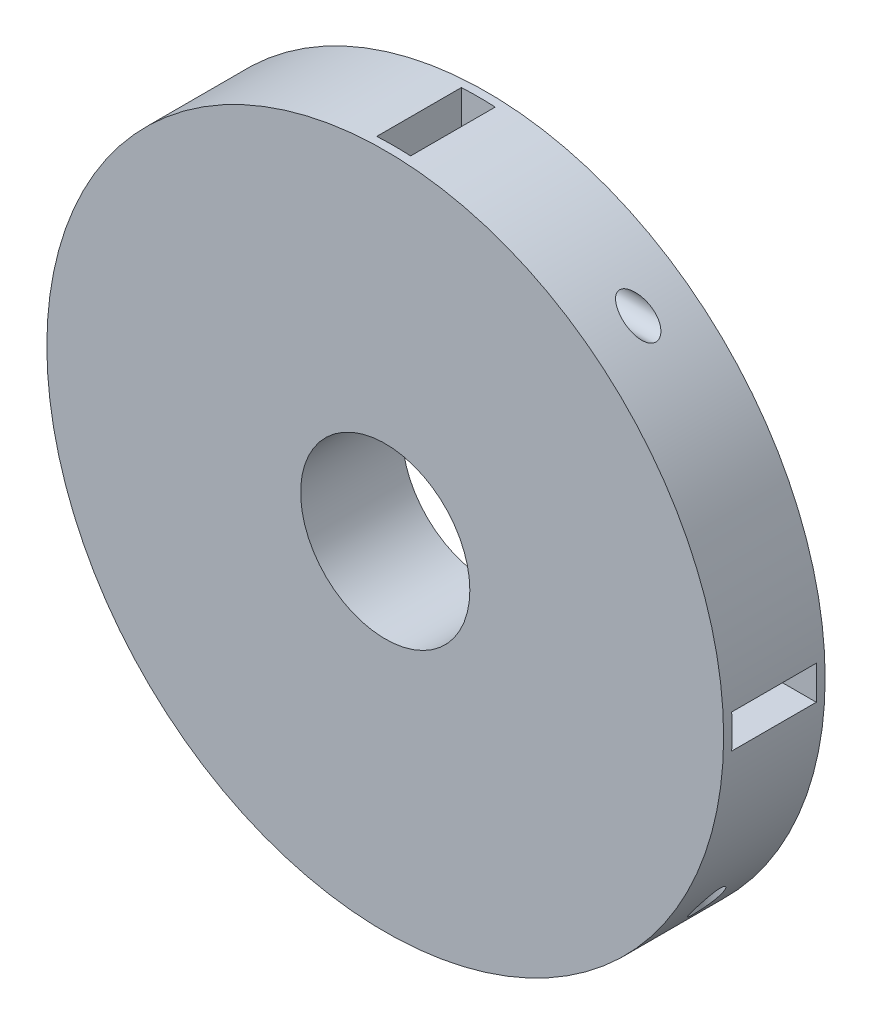
SolidWorks part; units mm, degrees
ref_plane "Front Plane" through (0, 0, 0) normal (0, 0, 1) x (1, 0, 0)
ref_plane "Top Plane" through (0, 0, 0) normal (0, 1, 0) x (1, 0, 0)
ref_plane "Right Plane" through (0, 0, 0) normal (1, 0, 0) x (0, 0, -1)
sketch "Sketch1" plane through (0, 0, 0) normal (0, 0, 1) x (1, 0, 0)
  circle A0 centre (0, 0) radius 100
  circle A1 centre (0, 0) radius 25
  dimension "D1" = 200
  dimension "D2" = 50
extrude "Boss-Extrude1" add sketch "Sketch1" along normal mid plane 30
sketch "Sketch2" plane through (0, 0, 0) normal (0, 0, 1) x (1, 0, 0)
  line L0 (0, -146.3534) -> (0, 146.3534) construction
  line L1 (187.0515, 0) -> (-187.0515, 0) construction
  line L2 (100, -29.0064) -> (100, 29.0064) construction
  line L3 (60, -5) -> (110, -5)
  line L4 (60, -5) -> (60, 5)
  line L5 (60, 5) -> (100, 5)
  line L7 (100, 5) -> (110, -5)
  line L20 (-5, -60) -> (-5, -110)
  line L21 (-5, -60) -> (5, -60)
  line L22 (5, -60) -> (5, -100)
  line L23 (5, -100) -> (-5, -110)
  line L24 (-60, 5) -> (-110, 5)
  line L25 (-60, 5) -> (-60, -5)
  line L26 (-60, -5) -> (-100, -5)
  line L27 (-100, -5) -> (-110, 5)
  line L28 (5, 60) -> (5, 110)
  line L29 (5, 60) -> (-5, 60)
  line L30 (-5, 60) -> (-5, 100)
  line L31 (-5, 100) -> (5, 110)
  circle A0 centre (0, 0) radius 100 construction
  circle A1 centre (0, 0) radius 100 construction
  point P5 (0, 0)
  point P6 (100, 0)
  point P9 (0, 0)
  point P19 (100, 0)
  point P22 (0, -100)
  point P26 (0, -100)
  point P28 (-100, 0)
  point P32 (-100, 0)
  point P34 (0, 100)
  point P38 (0, 100)
  point P40 (-5, 0.4636)
  point P41 (0, 0)
  dimension "D1" = 200
  dimension "D2" = 4
  dimension "D3" = 5
  dimension "D4" = 40
  dimension "D5" = 10
  dimension "D6" = 5
extrude "Cut-Extrude1" cut sketch "Sketch2" against normal mid plane 25
sketch "Sketch3" plane through (0, 0, 0) normal (0, 1, 0) x (1, 0, 0)
  line L0 (0, -89.4161) -> (0, 89.4161) construction
  line L2 (-155.125, 0) -> (155.125, 0) construction
  line L3 (60, -63.4515) -> (60, 63.4515) construction
  circle A0 centre (80, 0) radius 4
  point P4 (0, 0)
  point P8 (0, 0)
  point P11 (60, 0)
  dimension "D1" = 8
  dimension "D2" = 20
extrude "Cut-Extrude2" cut sketch "Sketch3" against normal blind 100 and the other way blind 25
sketch "Sketch4" plane through (0, 0, 0) normal (1, 0, 0) x (0, 0, -1)
  line L0 (-110.8945, 0) -> (110.8945, 0) construction
  line L1 (0, -132.0284) -> (0, 132.0284) construction
  line L3 (-84.1199, 60) -> (84.1199, 60) construction
  circle A0 centre (0, 80) radius 4
  point P4 (0, 0)
  point P8 (0, 0)
  point P11 (0, 60)
  dimension "D1" = 20
  dimension "D2" = 8
extrude "Cut-Extrude3" cut sketch "Sketch4" against normal blind 25 and the other way blind 100
sketch "Sketch5" plane through (0, 0, 0) normal (1, 0, 0) x (0, 0, -1)
  line L0 (-96.4192, 0) -> (96.4192, 0) construction
  line L1 (0, -127.4809) -> (0, 127.4809) construction
  line L2 (-60.1083, -60) -> (60.1083, -60) construction
  circle A0 centre (0, -80) radius 4
  point P4 (0, 0)
  point P8 (0, 0)
  point P11 (0, -60)
  dimension "D2" = 8
  dimension "D1" = 20
extrude "Cut-Extrude4" cut sketch "Sketch5" against normal blind 100 and the other way blind 25
sketch "Sketch6" plane through (0, 0, 0) normal (0, 1, 0) x (1, 0, 0)
  line L0 (-194.6438, 0) -> (194.6438, 0) construction
  line L2 (0, -98.3418) -> (0, 98.3418) construction
  line L3 (-60, -79.2543) -> (-60, 79.2543) construction
  circle A0 centre (-80, 0) radius 4
  point P4 (0, 0)
  point P8 (0, 0)
  point P11 (-60, 0)
  dimension "D1" = 20
  dimension "D2" = 8
extrude "Cut-Extrude5" cut sketch "Sketch6" against normal blind 25 and the other way blind 100
